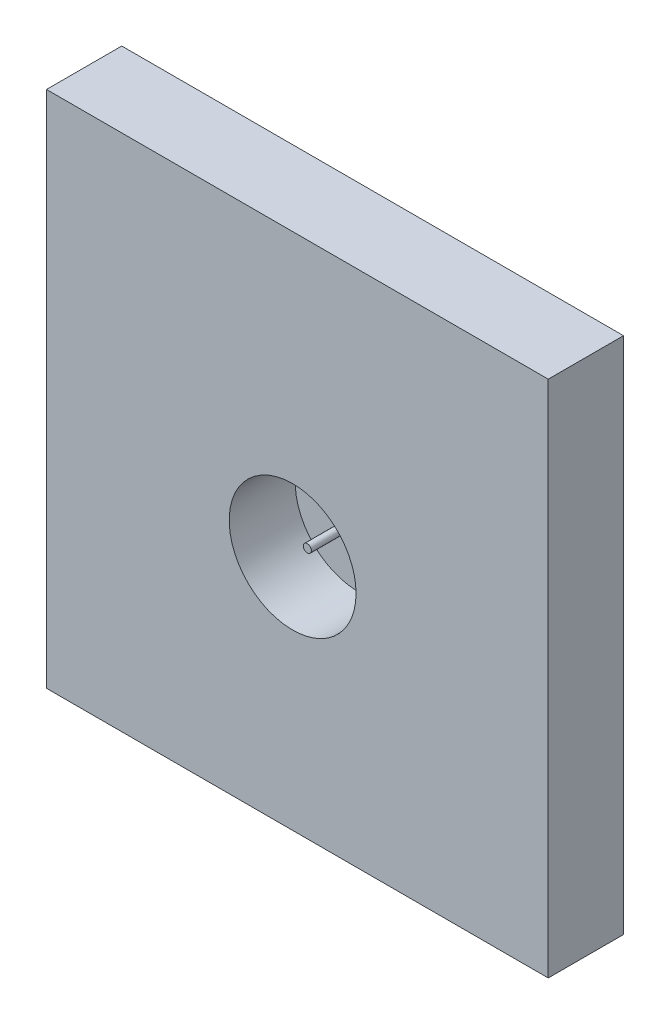
SolidWorks part; units mm, degrees
ref_plane "Front Plane" through (0, 0, 0) normal (0, 0, 1) x (1, 0, 0)
ref_plane "Top Plane" through (0, 0, 0) normal (0, 1, 0) x (1, 0, 0)
ref_plane "Right Plane" through (0, 0, 0) normal (1, 0, 0) x (0, 0, -1)
sketch "Sketch1" plane through (0, 0, 0) normal (1, 0, 0) x (0, 0, -1)
  line L1 (-943.5108, -6167.6517) -> (635.1912, -6167.6517)
  line L2 (-943.5108, -6167.6517) -> (-943.5108, 4711.3099)
  line L3 (-943.5108, 4711.3099) -> (635.1912, 4711.3099)
  line L4 (635.1912, -6167.6517) -> (635.1912, 4711.3099)
extrude "Boss-Extrude1" add sketch "Sketch1" along normal blind 6196 and the other way blind 4329
sketch "Sketch3" plane through (0, 0, 943.5108) normal (0, 0, 1) x (1, 0, 0)
  circle A0 centre (833.9306, -1197.1664) radius 1330.4493
extrude "Cut-Extrude1" cut sketch "Sketch3" against normal blind 1384
sketch "Sketch4" plane through (0, 0, -635.1912) normal (0, 0, -1) x (-1, 0, 0)
  circle A0 centre (-833.9306, -1197.1664) radius 84.8072
extrude "Boss-Extrude2" add sketch "Sketch4" against normal blind 1270
